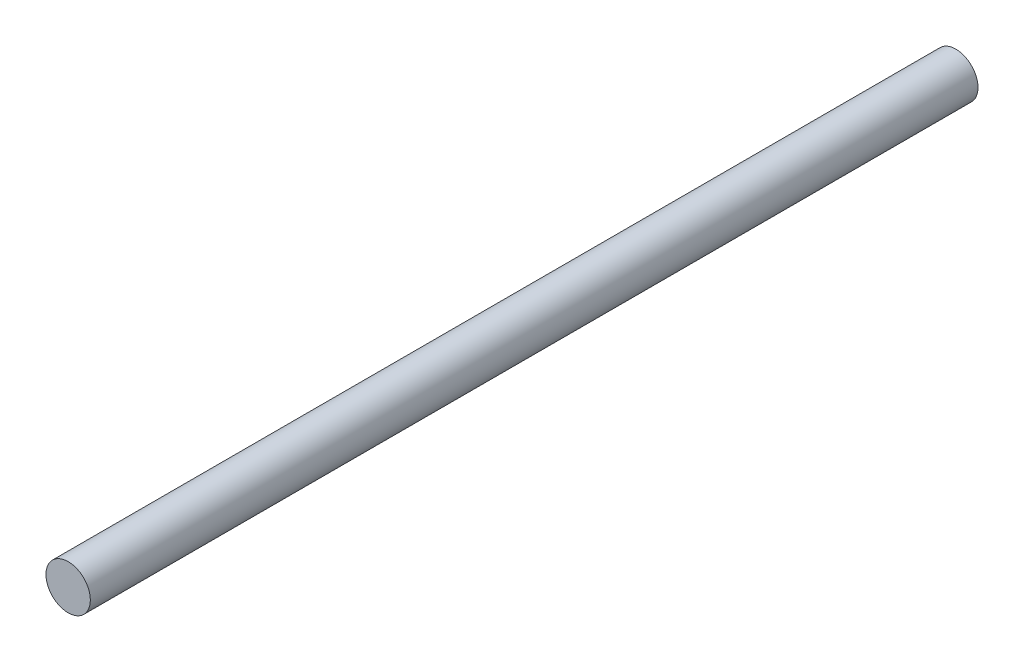
SolidWorks part; units mm, degrees
ref_plane "Front Plane" through (0, 0, 0) normal (0, 0, 1) x (1, 0, 0)
ref_plane "Top Plane" through (0, 0, 0) normal (0, 1, 0) x (1, 0, 0)
ref_plane "Right Plane" through (0, 0, 0) normal (1, 0, 0) x (0, 0, -1)
other "Configuration Table"
sketch "Sketch1" plane through (0, 0, 0) normal (0, 0, 1) x (1, 0, 0)
  circle A0 centre (0, 0) radius 2.5
extrude "SNS_kablo_D5" add sketch "Sketch1" against normal blind 100 from offset 40 separate body
